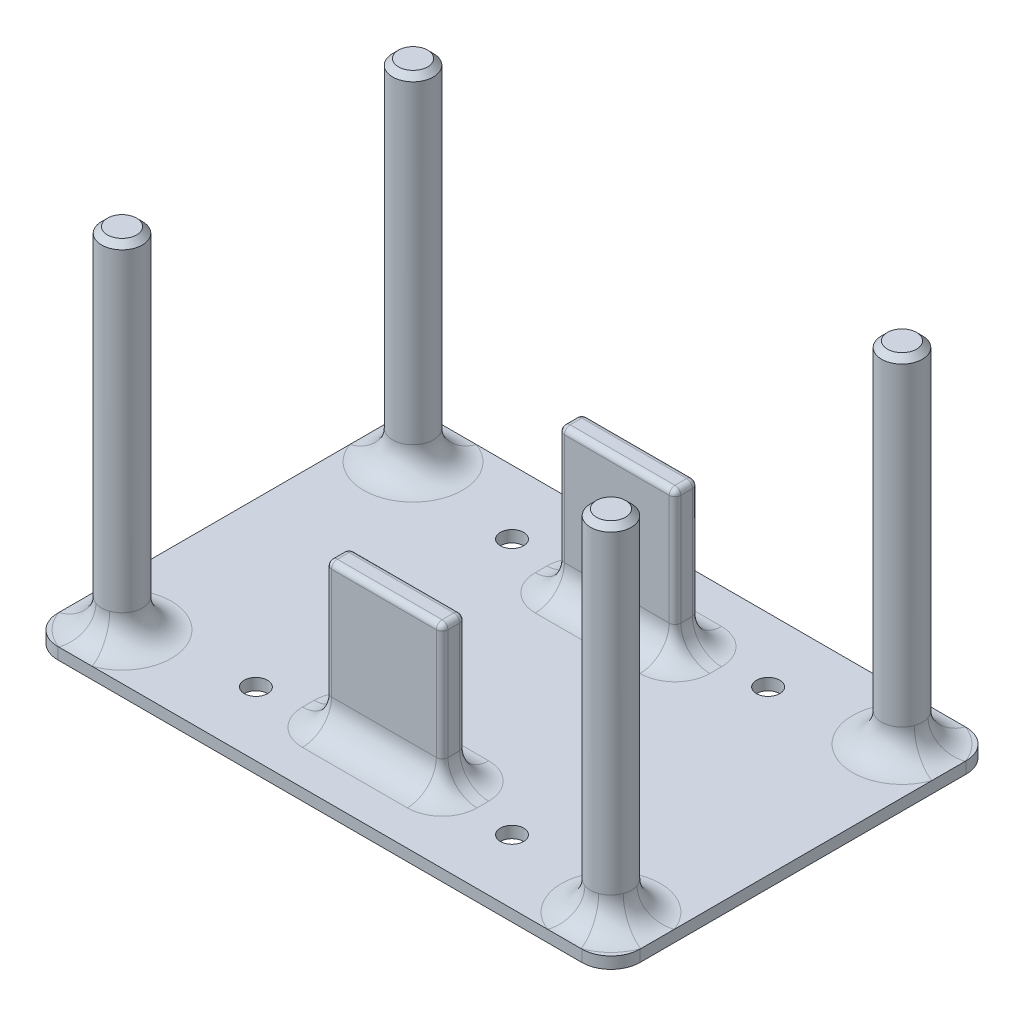
SolidWorks part; units mm, degrees
ref_plane "Front Plane" through (0, 0, 0) normal (0, 0, 1) x (1, 0, 0)
ref_plane "Top Plane" through (0, 0, 0) normal (0, 1, 0) x (1, 0, 0)
ref_plane "Right Plane" through (0, 0, 0) normal (1, 0, 0) x (0, 0, -1)
sketch "Sketch1" plane through (0, 0, 0) normal (0, 1, 0) x (1, 0, 0)
  line L1 (-35.9328, 54.7689) -> (54.0672, 54.7689)
  line L2 (-40.9328, 49.7689) -> (-40.9328, -6.2311)
  line L3 (-35.9328, -11.2311) -> (54.0672, -11.2311)
  line L4 (59.0672, 49.7689) -> (59.0672, -6.2311)
  arc A0 (54.0672, -11.2311) -> (59.0672, -6.2311) centre (54.0672, -6.2311) ccw
  arc A1 (54.0672, 54.7689) -> (59.0672, 49.7689) centre (54.0672, 49.7689) cw
  arc A2 (-40.9328, -6.2311) -> (-35.9328, -11.2311) centre (-35.9328, -6.2311) ccw
  arc A3 (-35.9328, 54.7689) -> (-40.9328, 49.7689) centre (-35.9328, 49.7689) ccw
  point P7 (59.0672, -11.2311)
  point P10 (59.0672, 54.7689)
  point P13 (-40.9328, -11.2311)
  dimension "D3" = 5
  dimension "D1" = 66
  dimension "D2" = 100
extrude "Boss-Extrude1" add sketch "Sketch1" along normal blind 2
sketch "Sketch3" plane through (0, 2, 0) normal (0, 1, 0) x (1, 0, 0)
  line L0 (-40.9328, 49.7689) -> (-40.9328, -6.2311) construction
  line L1 (54.0672, 54.7689) -> (-35.9328, 54.7689) construction
  line L2 (-35.9328, -11.2311) -> (54.0672, -11.2311) construction
  circle A0 centre (-32.9328, 46.7689) radius 3.5
  circle A1 centre (-32.9328, -3.2311) radius 3.5
  circle A2 centre (51.0672, -3.2311) radius 3.5
  circle A5 centre (51.0672, 46.7689) radius 3.5
  dimension "D1" = 7
  dimension "D2" = 8
  dimension "D3" = 8
  dimension "D4" = 7
  dimension "D5" = 8
  dimension "D6" = 8
extrude "Boss-Extrude2" add sketch "Sketch3" along normal blind 60
sketch "Sketch4" plane through (0, 2, 0) normal (0, 1, 0) x (1, 0, 0)
  line L0 (54.0672, 54.7689) -> (-35.9328, 54.7689) construction
  line L1 (0.0672, 43.7689) -> (18.0672, 43.7689)
  line L2 (-0.9328, 42.7689) -> (-0.9328, 40.7689)
  line L3 (0.0672, 39.7689) -> (18.0672, 39.7689)
  line L4 (19.0672, 42.7689) -> (19.0672, 40.7689)
  line L7 (-40.9328, 49.7689) -> (-40.9328, -6.2311) construction
  line L17 (19.0672, 0.7689) -> (19.0672, 2.7689)
  line L18 (0.0672, 3.7689) -> (18.0672, 3.7689)
  line L19 (-0.9328, 0.7689) -> (-0.9328, 2.7689)
  line L20 (0.0672, -0.2311) -> (18.0672, -0.2311)
  arc A4 (18.0672, 39.7689) -> (19.0672, 40.7689) centre (18.0672, 40.7689) ccw
  arc A5 (18.0672, 43.7689) -> (19.0672, 42.7689) centre (18.0672, 42.7689) cw
  arc A6 (-0.9328, 40.7689) -> (0.0672, 39.7689) centre (0.0672, 40.7689) ccw
  arc A7 (0.0672, 43.7689) -> (-0.9328, 42.7689) centre (0.0672, 42.7689) ccw
  arc A12 (0.0672, -0.2311) -> (-0.9328, 0.7689) centre (0.0672, 0.7689) cw
  arc A13 (-0.9328, 2.7689) -> (0.0672, 3.7689) centre (0.0672, 2.7689) cw
  arc A14 (18.0672, -0.2311) -> (19.0672, 0.7689) centre (18.0672, 0.7689) ccw
  arc A15 (18.0672, 3.7689) -> (19.0672, 2.7689) centre (18.0672, 2.7689) cw
  dimension "D1" = 4
  dimension "D2" = 20
  dimension "D3" = 11
  dimension "D4" = 40
extrude "Boss-Extrude3" add sketch "Sketch4" along normal blind 25
fillet "Fillet3" radius 5 4 edges at (51.0672, 2, -0.2689) (51.0672, 2, -43.2689) (-32.9328, 2, 6.7311) (-32.9328, 2, -43.2689)
sketch "Sketch6" plane through (0, 2, 0) normal (0, 1, 0) x (1, 0, 0)
  line L0 (-30.0605, -11.2311) -> (48.1949, -11.2311) construction
  line L1 (-40.9328, 43.8966) -> (-40.9328, -0.3588) construction
  line L2 (59.0672, -0.3588) -> (59.0672, 43.8966) construction
  line L4 (48.1949, 54.7689) -> (-30.0605, 54.7689) construction
  circle A0 centre (-12.9328, 43.7689) radius 2
  circle A1 centre (-12.9328, -0.2311) radius 2
  circle A2 centre (31.0672, -0.2311) radius 2
  circle A3 centre (31.0672, 43.7689) radius 2
  dimension "D1" = 44
  dimension "D2" = 11
  dimension "D3" = 28
  dimension "D4" = 28
  dimension "D5" = 28
  dimension "D6" = 28
  dimension "D7" = 11
  dimension "D8" = 11
extrude "Cut-Extrude1" cut sketch "Sketch6" against normal through all
fillet "Fillet4" radius 5 16 edges at (-0.6399, 2, -40.0618) (-0.9328, 2, -41.7689) (-0.6399, 2, -43.476) (9.0672, 2, -43.7689) (18.7743, 2, -43.476) (19.0672, 2, -41.7689) (18.7743, 2, -40.0618) (-0.6399, 2, -0.0618) (-0.9328, 2, -1.7689) (-0.6399, 2, -3.476) (9.0672, 2, -3.7689) (18.7743, 2, -3.476) (19.0672, 2, -1.7689) (18.7743, 2, -0.0618) (9.0672, 2, -39.7689) (9.0672, 2, 0.2311)
fillet "Fillet5" radius 1 16 edges at (-0.6399, 27, -40.0618) (-0.9328, 27, -41.7689) (-0.6399, 27, -43.476) (9.0672, 27, -43.7689) (18.7743, 27, -43.476) (19.0672, 27, -41.7689) (18.7743, 27, -40.0618) (-0.6399, 27, -0.0618) (-0.9328, 27, -1.7689) (-0.6399, 27, -3.476) (9.0672, 27, -3.7689) (18.7743, 27, -3.476) (19.0672, 27, -1.7689) (18.7743, 27, -0.0618) (9.0672, 27, -39.7689) (9.0672, 27, 0.2311)
chamfer "Chamfer1" distance 1 angle 45 4 edges at (-32.9328, 62, -43.2689) (51.0672, 62, -0.2689) (51.0672, 62, -43.2689) (-32.9328, 62, 6.7311)
